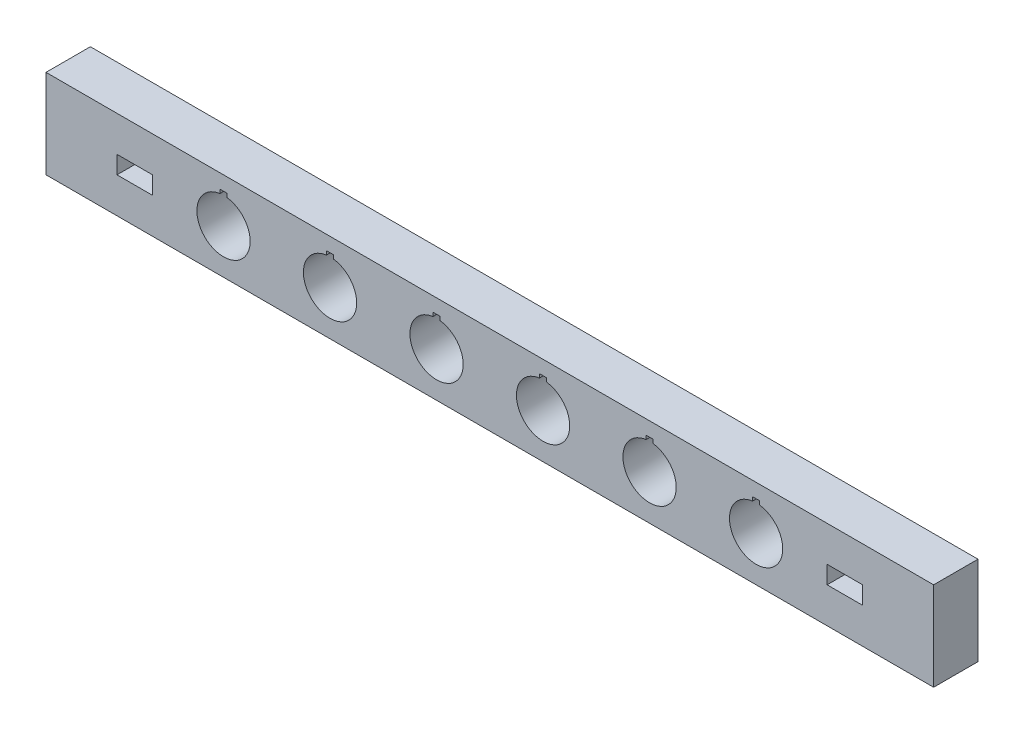
SolidWorks part; units mm, degrees
ref_plane "Front Plane" through (0, 0, 0) normal (0, 0, 1) x (1, 0, 0)
ref_plane "Top Plane" through (0, 0, 0) normal (0, 1, 0) x (1, 0, 0)
ref_plane "Right Plane" through (0, 0, 0) normal (1, 0, 0) x (0, 0, -1)
sketch "Sketch1" plane through (0, 0, 0) normal (0, 0, 1) x (1, 0, 0)
  line L1 (-450, 50) -> (450, 50)
  line L2 (-450, 50) -> (-450, -50)
  line L3 (-450, -50) -> (450, -50)
  line L4 (450, 50) -> (450, -50)
  line L5 (-450, 50) -> (450, -50) construction
  line L6 (-450, -50) -> (450, 50) construction
  point P0 (0, 0)
  dimension "D1" = 900
  dimension "D2" = 100
extrude "Boss-Extrude1" add sketch "Sketch1" along normal blind 50
sketch "Sketch2" plane through (0, 0, 50) normal (0, 0, 1) x (1, 0, 0)
  line L0 (-450, 50) -> (-450, -50) construction
  line L1 (450, 50) -> (-450, 50) construction
  line L2 (-420, 10) -> (-380, 10)
  line L3 (-420, 10) -> (-420, -10)
  line L4 (-420, -10) -> (-380, -10)
  line L5 (-380, 10) -> (-380, -10)
  line L6 (-420, 10) -> (-380, -10) construction
  line L7 (-420, -10) -> (-380, 10) construction
  line L8 (-180, 34) -> (-184, 34)
  line L9 (0, 50) -> (0, -50)
  line L10 (-450, -50) -> (450, -50) construction
  line L11 (380, 10) -> (380, -10)
  line L12 (420, 10) -> (380, 10)
  line L13 (420, 10) -> (420, -10)
  line L14 (420, -10) -> (380, -10)
  line L15 (-300, 34) -> (-296, 34)
  line L18 (-300, 34) -> (-304, 34)
  line L19 (-304, 29.7321) -> (-304, 34)
  line L22 (-296, 34) -> (-296, 29.7321)
  line L23 (-184, 29.7321) -> (-184, 34)
  line L24 (-176, 34) -> (-176, 29.7321)
  line L25 (-180, 34) -> (-176, 34)
  line L27 (-60, 34) -> (-64, 34)
  line L28 (-64, 29.7321) -> (-64, 34)
  line L29 (-56, 34) -> (-56, 29.7321)
  line L30 (-60, 34) -> (-56, 34)
  line L32 (60, 34) -> (56, 34)
  line L33 (56, 29.7321) -> (56, 34)
  line L34 (64, 34) -> (64, 29.7321)
  line L35 (60, 34) -> (64, 34)
  line L37 (180, 34) -> (176, 34)
  line L38 (176, 29.7321) -> (176, 34)
  line L39 (184, 34) -> (184, 29.7321)
  line L40 (180, 34) -> (184, 34)
  line L42 (300, 34) -> (296, 34)
  line L43 (296, 29.7321) -> (296, 34)
  line L44 (304, 34) -> (304, 29.7321)
  line L45 (300, 34) -> (304, 34)
  arc A0 (-304, 29.7321) -> (-296, 29.7321) centre (-300, 0) ccw
  arc A1 (-184, 29.7321) -> (-176, 29.7321) centre (-180, 0) ccw
  arc A2 (-64, 29.7321) -> (-56, 29.7321) centre (-60, 0) ccw
  arc A3 (56, 29.7321) -> (64, 29.7321) centre (60, 0) ccw
  arc A4 (176, 29.7321) -> (184, 29.7321) centre (180, 0) ccw
  arc A5 (296, 29.7321) -> (304, 29.7321) centre (300, 0) ccw
  point P14 (-400, 0)
  point P29 (0, 0)
  dimension "D1" = 6
  dimension "D2" = 150
  dimension "D3" = 40
  dimension "D4" = 20
  dimension "D5" = 50
  dimension "D6" = 40
  dimension "D7" = 34
  dimension "D8" = 4
  dimension "D10" = 6
extrude "Cut-Extrude1" cut sketch "Sketch2" against normal blind 50 contours A0 | A1 | A2 | A3 | A4 | A5 | L14 L13 L12 L11 | L3 L2 L5 L4
sketch "Sketch3" plane through (0, 50, 0) normal (0, 1, 0) x (1, 0, 0)
  line L1 (450, 0) -> (500, 0)
  line L2 (450, 0) -> (450, -50)
  line L3 (450, -50) -> (500, -50)
  line L4 (500, 0) -> (500, -50)
  line L5 (-450, 0) -> (-500, 0)
  line L6 (-450, 0) -> (-450, -50)
  line L7 (-450, -50) -> (-500, -50)
  line L8 (-500, 0) -> (-500, -50)
  dimension "D1" = 50
  dimension "D2" = 50
extrude "Boss-Extrude2" add sketch "Sketch3" against normal blind 100
